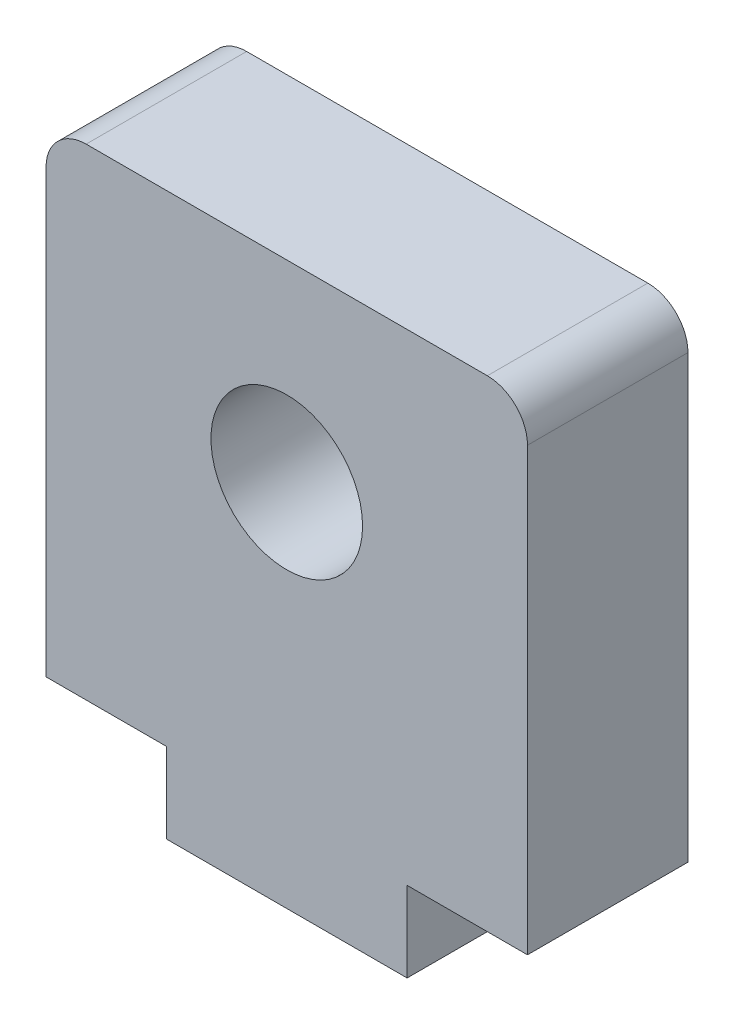
SolidWorks part; units mm, degrees
material "6061-T6 (SS)"
ref_plane "X-Y Datum" through (0, 0, 0) normal (0, 0, 1) x (1, 0, 0)
ref_plane "X-Z Datum" through (0, 0, 0) normal (0, 1, 0) x (1, 0, 0)
ref_plane "Y-Z Datum" through (0, 0, 0) normal (1, 0, 0) x (0, 0, -1)
sketch "Sketch1" plane through (0, 0, 0) normal (0, 0, 1) x (1, 0, 0)
  line L0 (0, 11.1125) -> (0, -11.1125) construction
  line L5 (-9.525, 11.1125) -> (9.525, 11.1125)
  line L6 (-9.525, 11.1125) -> (-9.525, -11.1125)
  line L7 (-9.525, -11.1125) -> (9.525, -11.1125)
  line L8 (9.525, 11.1125) -> (9.525, -11.1125)
  line L9 (-9.525, 11.1125) -> (9.525, -11.1125) construction
  line L10 (-9.525, -11.1125) -> (9.525, 11.1125) construction
  line L11 (-9.525, -7.9375) -> (9.525, -7.9375)
  line L12 (0, -7.9375) -> (0, -11.1125) construction
  line L14 (-4.7625, -7.9375) -> (4.7625, -7.9375)
  line L15 (-4.7625, -7.9375) -> (-4.7625, -11.1125)
  line L16 (-4.7625, -11.1125) -> (4.7625, -11.1125)
  line L17 (4.7625, -7.9375) -> (4.7625, -11.1125)
  line L18 (-4.7625, -7.9375) -> (4.7625, -11.1125) construction
  line L19 (-4.7625, -11.1125) -> (4.7625, -7.9375) construction
  circle A0 centre (0, 3.4925) radius 3
  point P0 (0, 0)
  point P14 (0, -9.525)
  dimension "D2" = 6
  dimension "D1" = 19.05
  dimension "D3" = 22.225
  dimension "D4" = 7.62
  dimension "D5" = 3.175
  dimension "D6" = 9.525
extrude "Boss-Extrude1" add sketch "Sketch1" along normal blind 6.35 contours L6 L11 L8 L5 A0 | L17 L11 L15 L7
fillet "Fillet1" radius 1.5875 2 edges at (9.525, 11.1125, 3.175) (-9.525, 11.1125, 3.175)
